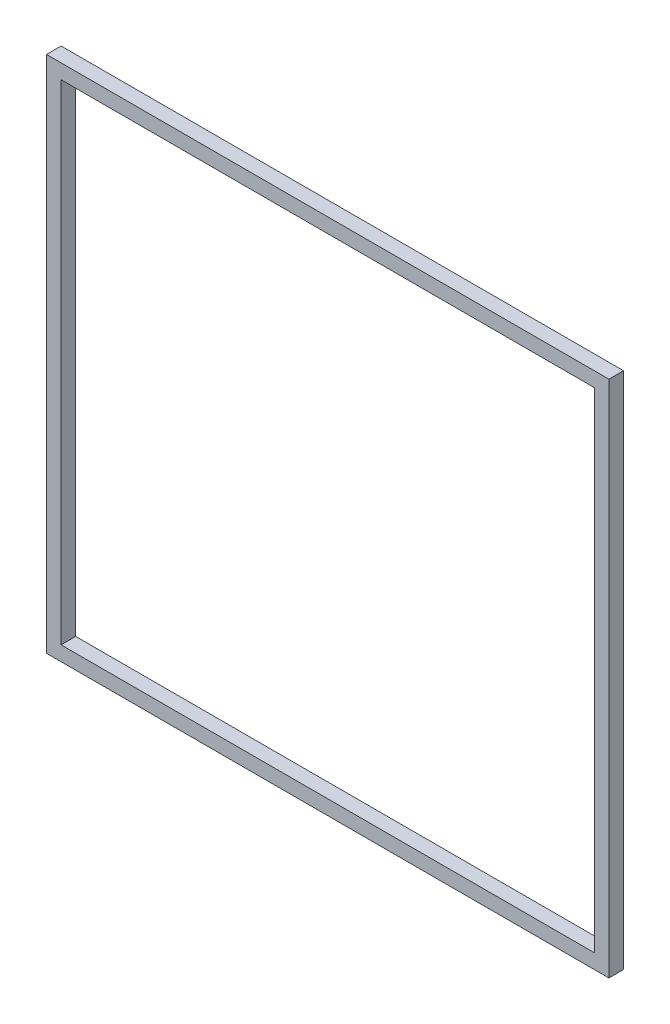
SolidWorks part; units mm, degrees
material "ABS"
ref_plane "Front Plane" through (0, 0, 0) normal (0, 0, 1) x (1, 0, 0)
ref_plane "Top Plane" through (0, 0, 0) normal (0, 1, 0) x (1, 0, 0)
ref_plane "Right Plane" through (0, 0, 0) normal (1, 0, 0) x (0, 0, -1)
sketch "Sketch1" plane through (0, 0, 0) normal (0, 0, 1) x (1, 0, 0)
  line L0 (0, 355) -> (0, 0) construction
  line L1 (-385, 355) -> (385, 355)
  line L2 (-385, 355) -> (-385, -355)
  line L3 (-385, -355) -> (385, -355)
  line L4 (385, 355) -> (385, -355)
  line L5 (0, 0) -> (0, -355) construction
  line L6 (-365, 335) -> (365, 335)
  line L7 (365, 335) -> (365, -335)
  line L8 (-365, -335) -> (365, -335)
  line L9 (-365, 335) -> (-365, -335)
  dimension "D1" = 710
  dimension "D2" = 770
  dimension "D3" = 20
extrude "Boss-Extrude1" add sketch "Sketch1" along normal blind 20
